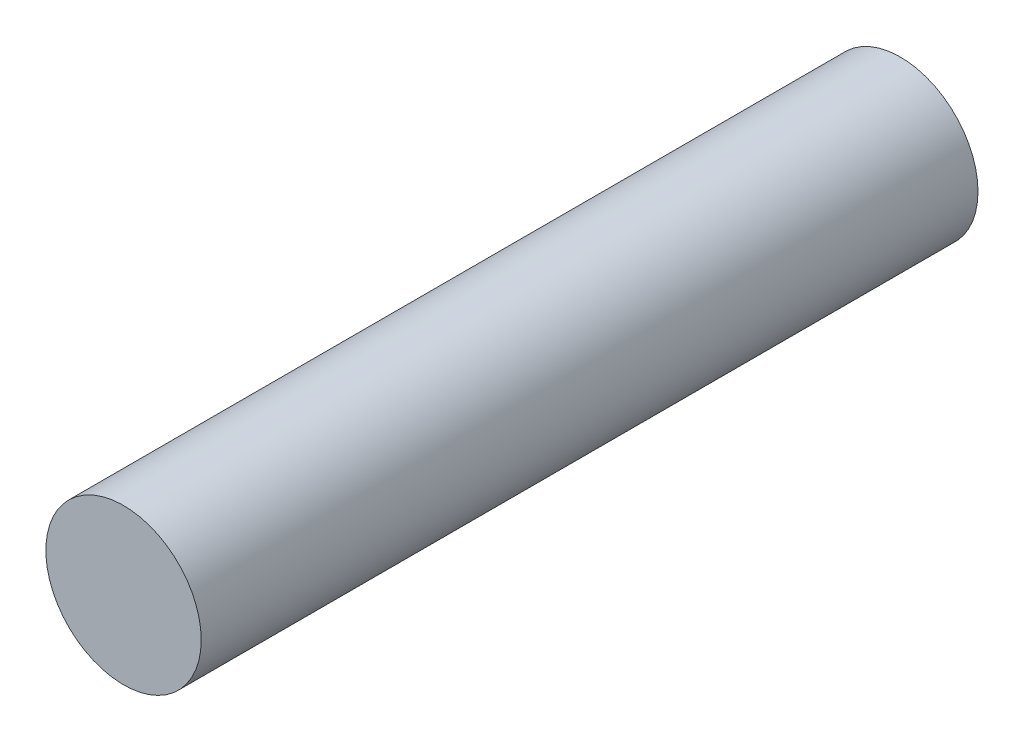
SolidWorks part; units mm, degrees
ref_plane "Přední rovina" through (0, 0, 0) normal (0, 0, 1) x (1, 0, 0)
ref_plane "Horní rovina" through (0, 0, 0) normal (0, 1, 0) x (1, 0, 0)
ref_plane "Pravá rovina" through (0, 0, 0) normal (1, 0, 0) x (0, 0, -1)
sketch "Sketch1" plane through (0, 0, 0) normal (0, 0, 1) x (1, 0, 0)
  circle A0 centre (0, 0) radius 5
  dimension "D1" = 10
extrude "Boss-Extrude1" add sketch "Sketch1" along normal blind 50 contours A0
